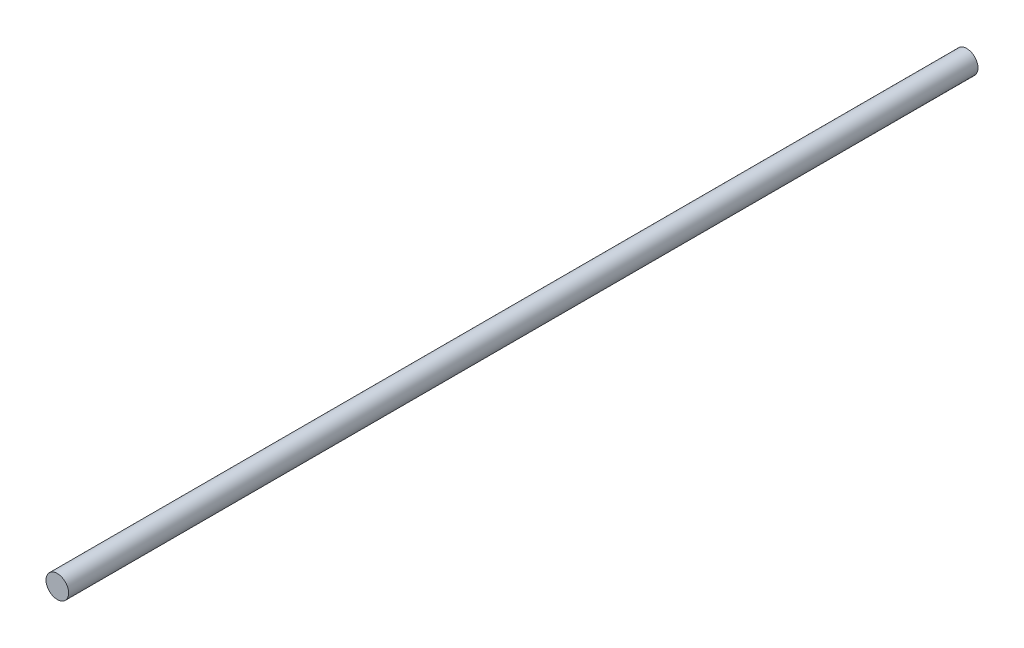
SolidWorks part; units mm, degrees
material "PVC Rigid"
ref_plane "Front Plane" through (0, 0, 0) normal (0, 0, 1) x (1, 0, 0)
ref_plane "Top Plane" through (0, 0, 0) normal (0, 1, 0) x (1, 0, 0)
ref_plane "Right Plane" through (0, 0, 0) normal (1, 0, 0) x (0, 0, -1)
sketch "Sketch1" plane through (0, 0, 0) normal (0, 0, 1) x (1, 0, 0)
  circle A0 centre (0, 0) radius 6
extrude "Boss-Extrude1" add sketch "Sketch1" along normal blind 482.6
